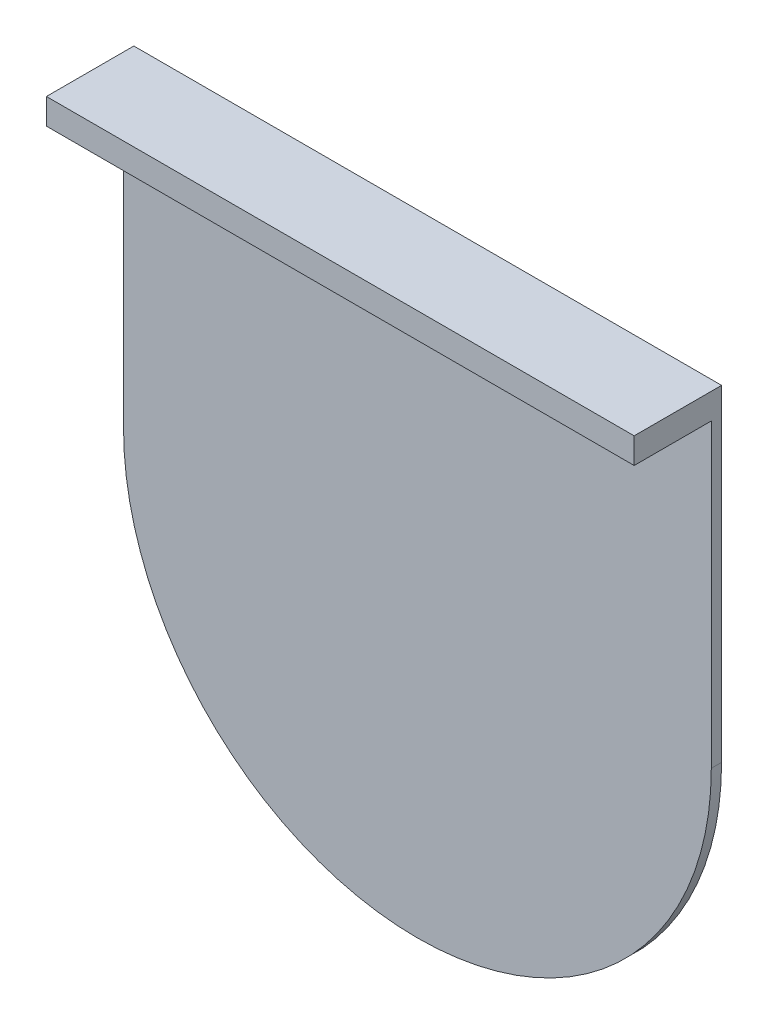
SolidWorks part; units mm, degrees
ref_plane "Front Plane" through (0, 0, 0) normal (0, 0, 1) x (1, 0, 0)
ref_plane "Top Plane" through (0, 0, 0) normal (0, 1, 0) x (1, 0, 0)
ref_plane "Right Plane" through (0, 0, 0) normal (1, 0, 0) x (0, 0, -1)
sketch "Sketch3" plane through (0, 0, 0) normal (0, 0, 1) x (1, 0, 0)
  line L0 (0, 0) -> (0, 120.65) construction
  line L1 (-57.15, 120.65) -> (57.15, 120.65)
  line L2 (57.15, 120.65) -> (57.15, 57.15)
  line L3 (-57.15, 120.65) -> (-57.15, 57.15)
  arc A0 (57.15, 57.15) -> (-57.15, 57.15) centre (0, 57.15) cw
  point P6 (0, 0)
  point P9 (0, 0)
  point P11 (0, 97.9407)
  point P12 (0, 0)
  dimension "D1" = 114.3
  dimension "D2" = 120.65
extrude "Boss-Extrude3" add sketch "Sketch3" along normal blind 2
sketch "Sketch4" plane through (0, 0, 2) normal (0, 0, 1) x (1, 0, 0)
  line L0 (57.15, 57.15) -> (57.15, 120.65) construction
  line L1 (-57.15, 120.65) -> (57.15, 120.65)
  line L2 (-57.15, 120.65) -> (-57.15, 115.65)
  line L3 (-57.15, 115.65) -> (57.15, 115.65)
  line L4 (57.15, 120.65) -> (57.15, 115.65)
  line L5 (0, 115.65) -> (0, 120.65) construction
  line L6 (-57.15, 118.15) -> (57.15, 118.15) construction
  point P228 (0, 118.15)
  dimension "D1" = 5
extrude "Boss-Extrude4" add sketch "Sketch4" along normal blind 15
